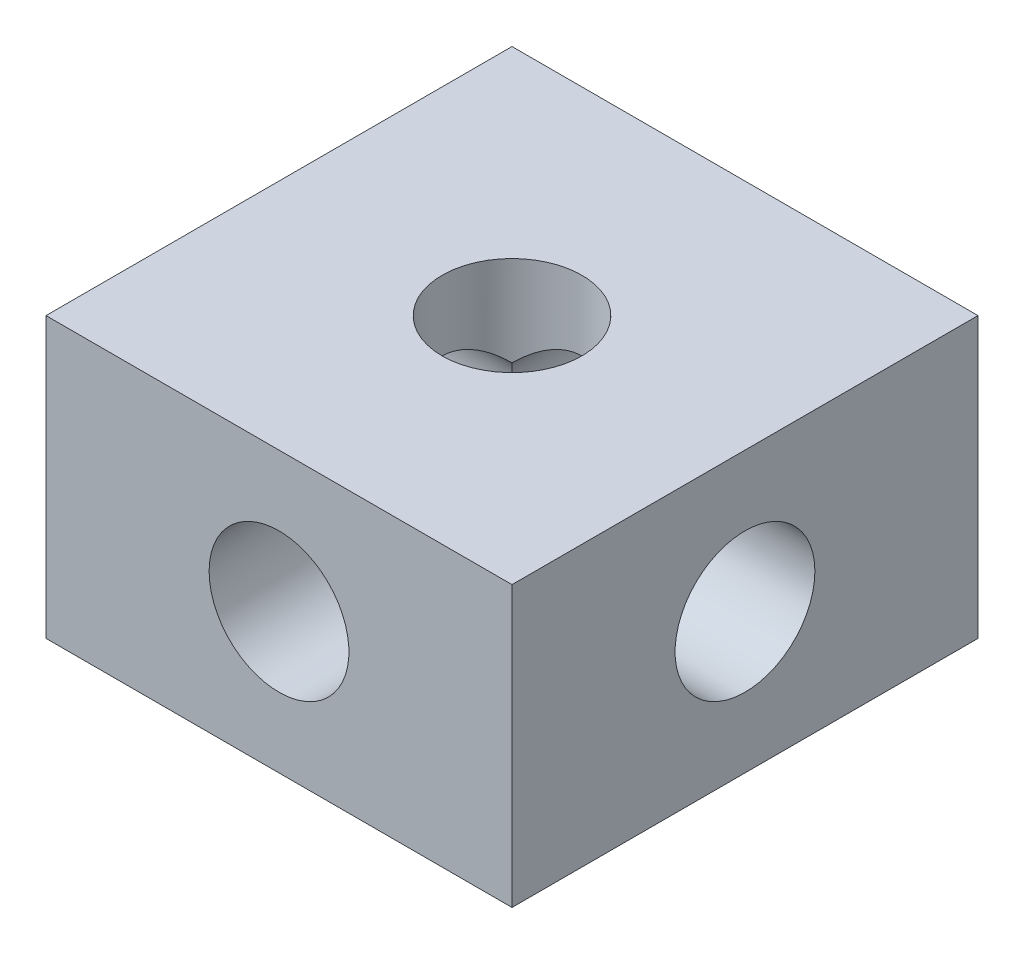
SolidWorks part; units mm, degrees
material "1060 合金"
ref_plane "前视基准面" through (0, 0, 0) normal (0, 0, 1) x (1, 0, 0)
ref_plane "上视基准面" through (0, 0, 0) normal (0, 1, 0) x (1, 0, 0)
ref_plane "右视基准面" through (0, 0, 0) normal (1, 0, 0) x (0, 0, -1)
other "Configuration Table"
sketch "草图1" plane through (0, 0, 0) normal (0, 1, 0) x (1, 0, 0)
  line L1 (-5, -5) -> (5, -5)
  line L2 (-5, -5) -> (-5, 5)
  line L3 (-5, 5) -> (5, 5)
  line L4 (5, -5) -> (5, 5)
  line L5 (-5, -5) -> (5, 5) construction
  line L6 (-5, 5) -> (5, -5) construction
  circle A0 centre (0, 0) radius 1.5
  point P0 (0, 0)
  dimension "D3" = 3
  dimension "D1" = 10
  dimension "D2" = 10
extrude "凸台-拉伸1" add sketch "草图1" along normal blind 6
sketch "草图2" plane through (0, 0, -5) normal (0, 0, -1) x (-1, 0, 0)
  line L0 (-5, 0) -> (5, 0) construction
  line L1 (5, 6) -> (5, 0) construction
  circle A0 centre (0, 3) radius 1.5
  dimension "D1" = 3
  dimension "D2" = 3
  dimension "D3" = 5
extrude "切除-拉伸1" cut sketch "草图2" against normal blind 10
sketch "草图3" plane through (5, 0, 0) normal (1, 0, 0) x (0, 0, -1)
  line L0 (-5, 0) -> (5, 0) construction
  line L1 (5, 6) -> (5, 0) construction
  circle A0 centre (0, 3) radius 1.5
  dimension "D1" = 3
  dimension "D2" = 3
  dimension "D3" = 5
extrude "切除-拉伸2" cut sketch "草图3" against normal blind 10
